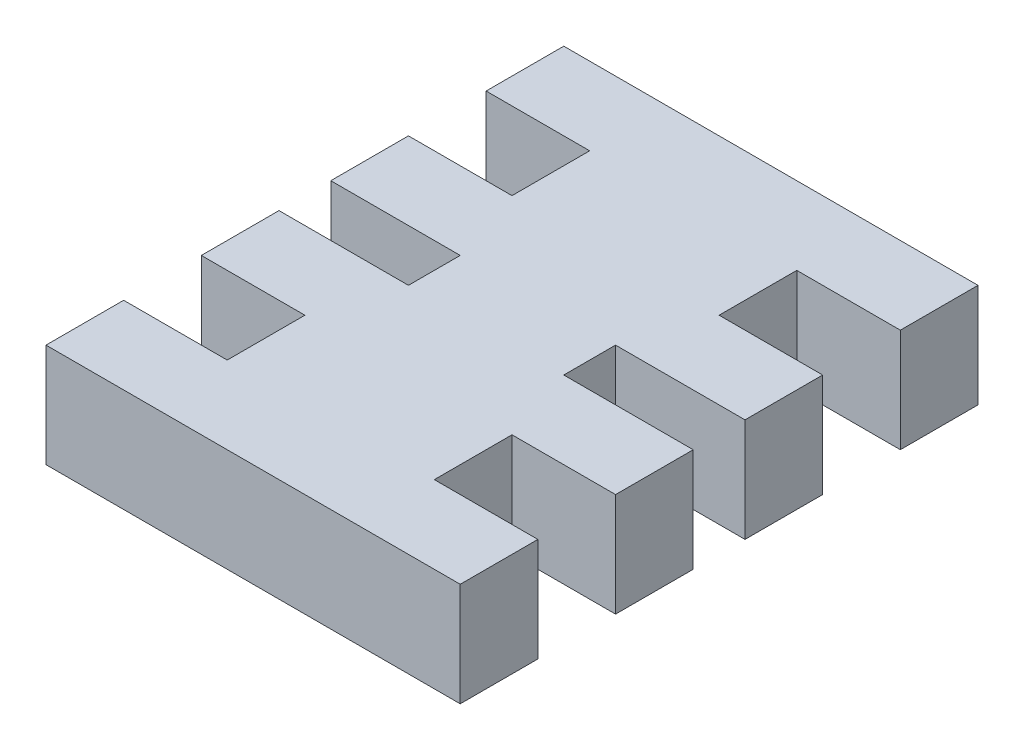
SolidWorks part; units mm, degrees
ref_plane "Front Plane" through (0, 0, 0) normal (0, 0, 1) x (1, 0, 0)
ref_plane "Top Plane" through (0, 0, 0) normal (0, 1, 0) x (1, 0, 0)
ref_plane "Right Plane" through (0, 0, 0) normal (1, 0, 0) x (0, 0, -1)
sketch "Sketch2" plane through (0, 0, 0) normal (0, 1, 0) x (1, 0, 0)
  line L0 (40, 50) -> (-40, 50)
  line L5 (-40, 50) -> (-40, 35)
  line L6 (-40, 35) -> (-20, 35)
  line L7 (-20, 35) -> (-20, 20)
  line L8 (-20, 20) -> (-40, 20)
  line L9 (-40, 20) -> (-40, 5)
  line L10 (-40, 5) -> (-15, 5)
  line L11 (-15, 5) -> (-15, -5)
  line L12 (0, 0) -> (-153.4267, 0) construction
  line L13 (0, 0) -> (0, -83.4838) construction
  line L14 (-40, -5) -> (-15, -5)
  line L15 (-40, -20) -> (-40, -5)
  line L16 (-20, -20) -> (-40, -20)
  line L17 (-20, -35) -> (-20, -20)
  line L18 (-40, -35) -> (-20, -35)
  line L19 (-40, -50) -> (-40, -35)
  line L20 (40, -50) -> (-40, -50)
  line L21 (40, -50) -> (40, -35)
  line L22 (40, -35) -> (20, -35)
  line L23 (20, -35) -> (20, -20)
  line L24 (20, -20) -> (40, -20)
  line L25 (40, -20) -> (40, -5)
  line L26 (40, -5) -> (15, -5)
  line L27 (15, 5) -> (15, -5)
  line L28 (40, 5) -> (15, 5)
  line L29 (40, 20) -> (40, 5)
  line L30 (20, 20) -> (40, 20)
  line L31 (20, 35) -> (20, 20)
  line L32 (40, 35) -> (20, 35)
  line L33 (40, 50) -> (40, 35)
  point P0 (15, 0)
  point P14 (-15, 0)
  point P22 (0, -50)
  point P35 (0, 50)
  dimension "D1" = 50
  dimension "D2" = 15
  dimension "D3" = 15
  dimension "D4" = 15
  dimension "D6" = 40
  dimension "D7" = 20
  dimension "D8" = 25
extrude "Boss-Extrude1" add sketch "Sketch2" along normal blind 20 contours L0 L5 L6 L7 L8 L9 L10 L11 L14 L15 L16 L17 L18 L19 L20 L21 L22 L23 L24 L25 L26 L27 L28 L29 L30 L31 L32 L33
